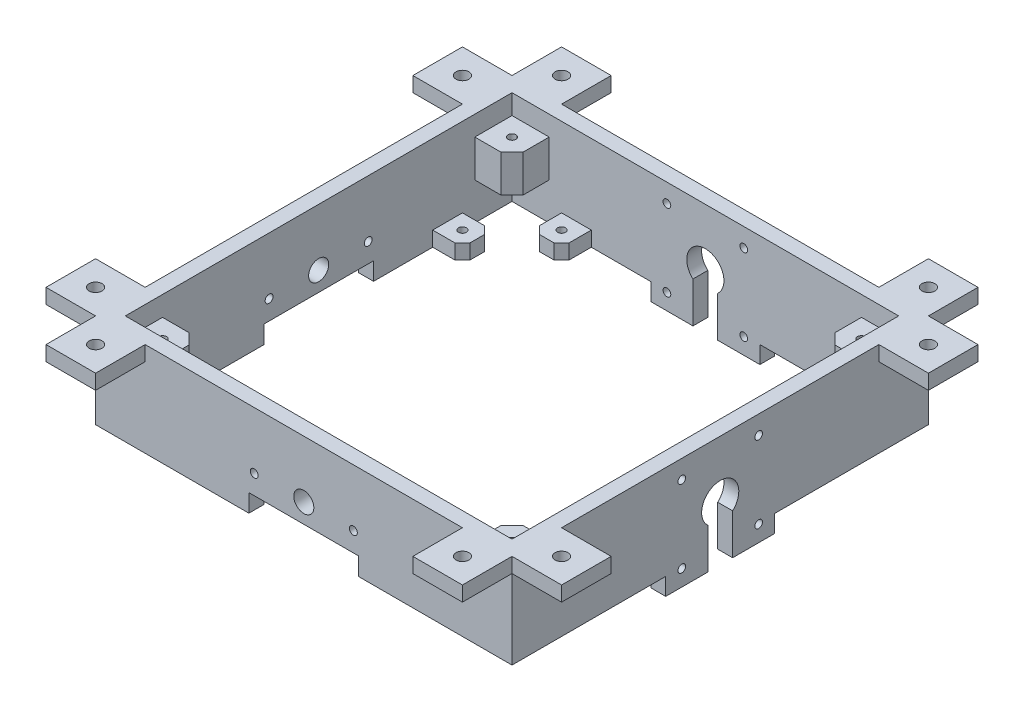
SolidWorks part; units mm, degrees
ref_plane "前视基准面" through (0, 0, 0) normal (0, 0, 1) x (1, 0, 0)
ref_plane "上视基准面" through (0, 0, 0) normal (0, 1, 0) x (1, 0, 0)
ref_plane "右视基准面" through (0, 0, 0) normal (1, 0, 0) x (0, 0, -1)
sketch "草图1" plane through (0, 0, 0) normal (0, 1, 0) x (1, 0, 0)
  line L1 (-84, -84) -> (84, -84)
  line L2 (-84, -84) -> (-84, 84)
  line L3 (-84, 84) -> (84, 84)
  line L4 (84, -84) -> (84, 84)
  line L5 (-84, -84) -> (84, 84) construction
  line L6 (-84, 84) -> (84, -84) construction
  line L7 (-78, -78) -> (78, -78)
  line L8 (-78, -78) -> (-78, 78)
  line L9 (-78, 78) -> (78, 78)
  line L10 (78, -78) -> (78, 78)
  line L11 (-78, -78) -> (78, 78) construction
  line L12 (-78, 78) -> (78, -78) construction
  point P0 (0, 0)
  point P6 (0, 0)
  dimension "D1" = 168
  dimension "D2" = 168
  dimension "D3" = 6
extrude "凸台-拉伸1" add sketch "草图1" along normal blind 38
ref_plane "基准面1" through (0, 30, 0) normal (0, -1, 0) x (-1, 0, 0)
sketch "草图2" plane through (0, 30, 0) normal (0, 1, 0) x (1, 0, 0)
  line L0 (-63, 67.3841) -> (-67.3841, 63) construction
  line L1 (-78, 78) -> (-63, 78) construction
  line L2 (-78, 78) -> (-78, 63) construction
  line L3 (-78, 63) -> (-63, 63) construction
  line L4 (-63, 78) -> (-63, 63) construction
  line L5 (-67.3841, 63) -> (-78, 63)
  line L6 (-78, 63) -> (-78, 78)
  line L7 (-78, 78) -> (-63, 78)
  line L8 (-63, 78) -> (-63, 67.3841)
  line L9 (-63, 67.3841) -> (-67.3841, 63)
  line L10 (67.3841, 63) -> (63, 67.3841)
  line L11 (63, 67.3841) -> (63, 78)
  line L12 (63, 78) -> (78, 78)
  line L13 (78, 78) -> (78, 63)
  line L14 (78, 63) -> (67.3841, 63)
  line L15 (63, -67.3841) -> (67.3841, -63)
  line L16 (67.3841, -63) -> (78, -63)
  line L17 (78, -63) -> (78, -78)
  line L18 (78, -78) -> (63, -78)
  line L19 (63, -78) -> (63, -67.3841)
  line L20 (-67.3841, -63) -> (-63, -67.3841)
  line L21 (-63, -67.3841) -> (-63, -78)
  line L22 (-63, -78) -> (-78, -78)
  line L23 (-78, -78) -> (-78, -63)
  line L24 (-78, -63) -> (-67.3841, -63)
  point P25 (0, 0)
  dimension "D1" = 15
  dimension "D2" = 15
  dimension "D3" = 45
  dimension "D5" = 6.2
  dimension "D4" = 4
extrude "凸台-拉伸2" add sketch "草图2" against normal blind 15
sketch "草图3" plane through (0, 15, 0) normal (0, -1, 0) x (-1, 0, 0)
  line L0 (78, 70.5) -> (63, 70.5) construction
  line L1 (78, 78) -> (78, 63) construction
  line L2 (63, 67.3841) -> (63, 78) construction
  line L3 (70.5, 78) -> (70.5, 63) construction
  line L4 (63, 78) -> (78, 78) construction
  line L5 (78, 63) -> (67.3841, 63) construction
  circle A0 centre (70.5, 70.5) radius 1.6
  dimension "D1" = 3.2
extrude "切除-拉伸1" cut sketch "草图3" against normal through all
sketch "草图4" plane through (0, 30, 0) normal (0, -1, 0) x (1, 0, 0)
  circle A0 centre (-70.5, -70.5) radius 3.1
  dimension "D1" = 6.2
extrude "切除-拉伸2" [suppressed] cut sketch "草图4" along normal blind 5
sketch "草图6" plane through (0, 0, 0) normal (0, 0, 1) x (1, 0, 0)
  line L0 (0, 0) -> (0, 38) construction
  line L1 (-84, 38) -> (84, 38) construction
pattern_circular "阵列(圆周)1" count 4 every 90 about axis through (0, 0, 0) along (0, 1, 0) of "切除-拉伸1"
sketch "草图8" plane through (0, 38, 0) normal (0, 1, 0) x (1, 0, 0)
  line L0 (-84, 84) -> (-84, 64)
  line L1 (-84, 84) -> (-84, -84) construction
  line L2 (-84, 64) -> (-104, 64)
  line L3 (-104, 64) -> (-104, 84)
  line L4 (-104, 84) -> (-84, 84)
  line L5 (-94, 84) -> (-94, 64) construction
  line L6 (-104, 74) -> (-94, 74) construction
  circle A0 centre (-94, 74) radius 2.6
  dimension "D3" = 5.2
  dimension "D1" = 20
  dimension "D2" = 20
extrude "凸台-拉伸3" add sketch "草图8" against normal blind 6
sketch "草图9" plane through (0, 38, 0) normal (0, 1, 0) x (1, 0, 0)
  line L0 (-84, 84) -> (-84, 104) construction
  line L1 (-84, 104) -> (-64, 104) construction
  line L2 (-64, 104) -> (-64, 84) construction
  line L3 (84, 84) -> (-104, 84) construction
  line L4 (-64, 84) -> (-84, 84) construction
  line L5 (-74, 104) -> (-74, 84) construction
  line L6 (-84, 94) -> (-64, 94) construction
  line L7 (-84, 84) -> (-84, 104)
  line L8 (-84, 104) -> (-64, 104)
  line L9 (-64, 104) -> (-64, 84)
  line L10 (-64, 84) -> (-84, 84)
  circle A0 centre (-74, 94) radius 2.6
  dimension "D3" = 5.2
  dimension "D1" = 20
  dimension "D2" = 20
extrude "凸台-拉伸4" add sketch "草图9" against normal blind 6
pattern_circular "阵列(圆周)2" count 4 every 90 about axis through (0, 0, 0) along (0, 1, 0) of "凸台-拉伸3", "凸台-拉伸4"
sketch "草图10" plane through (0, 0, -84) normal (0, 0, -1) x (-1, 0, 0)
  line L0 (0, 38) -> (0, 0) construction
  line L1 (22, 0) -> (-22, 0)
  line L2 (-84, 0) -> (84, 0) construction
  line L3 (-22, 0) -> (-22, -7)
  line L4 (-22, -7) -> (22, -7)
  line L5 (22, 0) -> (22, -7)
  point P10 (0, -7)
  dimension "D1" = 44
  dimension "D2" = 7
extrude "凸台-拉伸5" add sketch "草图10" against normal blind 6
sketch "草图11" plane through (0, 0, -84) normal (0, 0, -1) x (-1, 0, 0)
  line L0 (0, 38) -> (0, -7) construction
  line L1 (-22, -7) -> (22, -7) construction
  line L2 (-22, 15) -> (21.9657, 15) construction
  line L3 (-22, -7) -> (-22, 37) construction
  line L4 (-22, 37) -> (21.9154, 37) construction
  line L5 (21.9154, 37) -> (22, 0) construction
  line L6 (-5, -7) -> (-5, 9.4098)
  line L7 (-5, -7) -> (5, -7)
  line L8 (5, -7) -> (5, 9.4098)
  line L9 (0, 0) -> (0, 38) construction
  circle A0 centre (-15.5, 30.5) radius 1.55
  circle A1 centre (15.5, 30.5) radius 1.55
  circle A2 centre (15.5, -0.5) radius 1.55
  circle A3 centre (-15.5, -0.5) radius 1.55
  circle A4 centre (0, 15) radius 7.5 construction
  arc A5 (-5, 9.4098) -> (5, 9.4098) centre (0, 15) cw
  dimension "D1" = 3.1
  dimension "D2" = 31
  dimension "D4" = 31
  dimension "D5" = 15
  dimension "D7" = 22
  dimension "D3" = 44
  dimension "D6" = 10
extrude "切除-拉伸3" cut sketch "草图11" against normal blind 6
pattern_circular "阵列(圆周)3" count 2 every 90 about axis through (0, 0, 0) along (0, 1, 0) of "凸台-拉伸5", "切除-拉伸3"
sketch "草图12" plane through (0, 0, 84) normal (0, 0, 1) x (1, 0, 0)
  line L0 (0, 0) -> (0, 38) construction
  line L1 (22.15, 0) -> (-22.15, 0)
  line L2 (-84, 0) -> (84, 0) construction
  line L3 (-22.15, 0) -> (-22.15, 7.2)
  line L4 (-22.15, 7.2) -> (22.15, 7.2)
  line L5 (22.15, 0) -> (22.15, 7.2)
  line L7 (-22.15, 15) -> (22.15, 15) construction
  line L8 (22, -7) -> (5, -7) construction
  circle A0 centre (0, 15) radius 4.05
  point P12 (0, 7.2)
  dimension "D4" = 8.1
  dimension "D1" = 7.2
  dimension "D2" = 44.3
  dimension "D3" = 22
extrude "切除-拉伸4" cut sketch "草图12" against normal blind 6
sketch "草图16" plane through (0, 0, 84) normal (0, 0, 1) x (1, 0, 0)
  line L0 (-21.8805, 15) -> (21.8805, 15) construction
  line L1 (0, 35.7429) -> (0, -13.3197) construction
  circle A0 centre (-20, 15) radius 1.6
  circle A1 centre (20, 15) radius 1.6
  dimension "D1" = 3.2
  dimension "D2" = 40
extrude "切除-拉伸6" cut sketch "草图16" against normal blind 6
pattern_circular "阵列(圆周)4" count 2 every 90 about axis through (0, 0, 0) along (0, 1, 0) of "切除-拉伸4", "切除-拉伸6"
sketch "草图13" plane through (0, 0, 0) normal (0, -1, 0) x (1, 0, 0)
  line L0 (-78, 22.15) -> (-78, 78) construction
  line L1 (-78, 58) -> (-66, 58)
  line L2 (-78, 58) -> (-78, 46)
  line L3 (-78, 46) -> (-66, 46)
  line L4 (-66, 58) -> (-66, 46)
  line L5 (-78, 78) -> (-22.15, 78) construction
  line L6 (-78, 78) -> (78, -78) construction
  line L7 (-46, 78) -> (-46, 66)
  line L8 (-58, 66) -> (-46, 66)
  line L9 (-58, 78) -> (-58, 66)
  line L10 (-58, 78) -> (-46, 78)
  dimension "D1" = 12
  dimension "D2" = 12
  dimension "D3" = 20
extrude "凸台-拉伸6" add sketch "草图13" against normal blind 6
sketch "草图15" plane through (0, 0, 0) normal (0, -1, 0) x (1, 0, 0)
  line L0 (-66, 52) -> (-84, 52) construction
  line L1 (-66, 46) -> (-66, 58) construction
  line L2 (-84, 22.15) -> (-84, 84) construction
  line L3 (-72, 58) -> (-72, 46) construction
  line L4 (-66, 58) -> (-78, 58) construction
  line L5 (-78, 46) -> (-66, 46) construction
  line L6 (-78, 78) -> (78, -78) construction
  circle A0 centre (-72, 52) radius 1.6
  circle A1 centre (-52, 72) radius 1.6
  dimension "D1" = 3.2
extrude "切除-拉伸5" cut sketch "草图15" against normal blind 6
chamfer "倒角1" distance 3 angle 45 4 edges at (-66, 3, 46) (-66, 3, 58) (-46, 3, 66) (-58, 3, 66)
pattern_circular "阵列(圆周)5" count 4 over 360 about axis through (0, 0, 0) along (0, 1, 0) of "凸台-拉伸6", "切除-拉伸5", "倒角1"
